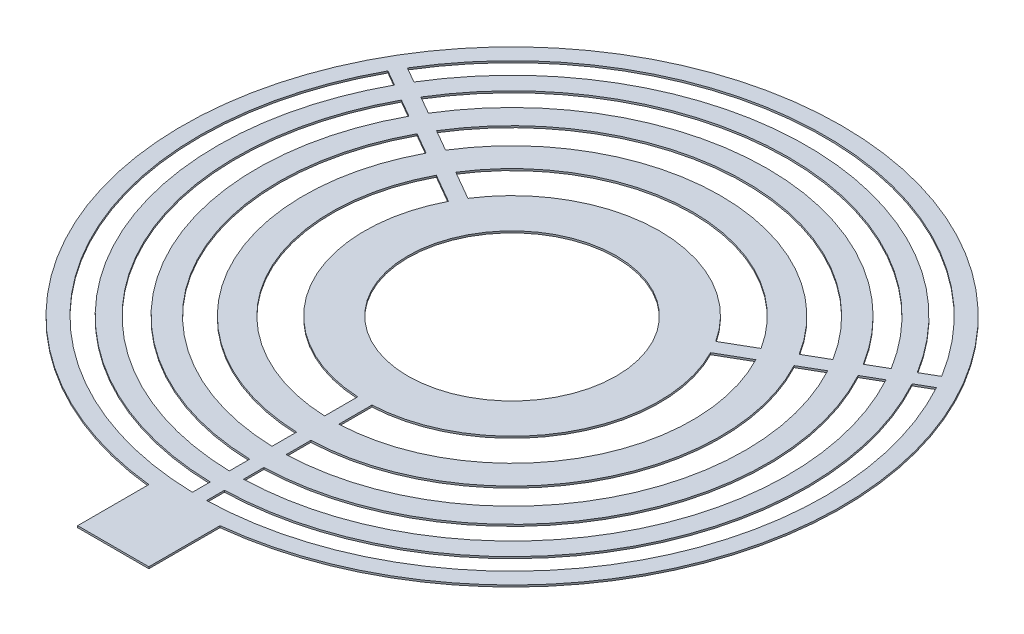
SolidWorks part; units mm, degrees
ref_plane "前视基准面" through (0, 0, 0) normal (0, 0, 1) x (1, 0, 0)
ref_plane "上视基准面" through (0, 0, 0) normal (0, 1, 0) x (1, 0, 0)
ref_plane "右视基准面" through (0, 0, 0) normal (1, 0, 0) x (0, 0, -1)
other "Configuration Table"
sketch "草图1" plane through (0, 0, 0) normal (0, 1, 0) x (1, 0, 0)
  line L0 (0, 0) -> (0, -29.29) construction
  line L1 (-2, -41.3717) -> (-2, -50.6906)
  line L2 (2, -41.3717) -> (2, -50.6906)
  line L3 (-10, -92.0886) -> (-10, -112.0886)
  line L4 (-10, -112.0886) -> (10, -112.0886)
  line L5 (10, -112.0886) -> (10, -92.0886)
  line L6 (-34.8289, 22.4179) -> (-42.8993, 27.0773)
  line L7 (-36.8289, 18.9538) -> (-44.8993, 23.6132)
  line L8 (36.8289, 18.9538) -> (44.8993, 23.6132)
  line L9 (34.8289, 22.4179) -> (42.8993, 27.0773)
  line L10 (51.7022, 27.5409) -> (57.6982, 31.0027)
  line L11 (49.7022, 31.005) -> (55.6982, 34.4668)
  line L12 (63.1132, 34.129) -> (68.0946, 37.005)
  line L13 (61.1132, 37.5931) -> (66.0946, 40.4691)
  line L14 (72.7293, 39.6809) -> (77.0779, 42.1916)
  line L15 (70.7293, 43.145) -> (75.0779, 45.6557)
  line L16 (-49.7022, 31.005) -> (-55.6982, 34.4668)
  line L17 (-51.7022, 27.5409) -> (-57.6982, 31.0027)
  line L18 (-61.1132, 37.5931) -> (-66.0946, 40.4691)
  line L19 (-63.1132, 34.129) -> (-68.0946, 37.005)
  line L20 (-70.7293, 43.145) -> (-75.0779, 45.6557)
  line L21 (-72.7293, 39.6809) -> (-77.0779, 42.1916)
  line L22 (-2, -58.5458) -> (-2, -65.4695)
  line L23 (2, -58.5458) -> (2, -65.4695)
  line L24 (2, -71.7221) -> (2, -77.4742)
  line L25 (-2, -71.7221) -> (-2, -77.4742)
  line L26 (2, -82.8259) -> (2, -87.8472)
  line L27 (-2, -82.8259) -> (-2, -87.8472)
  line L28 (0, -37.0978) -> (0, -55.5164) construction
  circle A0 centre (0, 0) radius 29.29
  arc A1 (2, -41.3717) -> (36.8289, 18.9538) centre (0, 0) ccw
  arc A2 (2, -50.6906) -> (44.8993, 23.6132) centre (0, 0) ccw
  arc A3 (2, -58.5458) -> (51.7022, 27.5409) centre (0, 0) ccw
  arc A4 (2, -65.4695) -> (57.6982, 31.0027) centre (0, 0) ccw
  arc A5 (2, -71.7221) -> (63.1132, 34.129) centre (0, 0) ccw
  arc A6 (2, -77.4742) -> (68.0946, 37.005) centre (0, 0) ccw
  arc A7 (2, -82.8259) -> (72.7293, 39.6809) centre (0, 0) ccw
  arc A8 (2, -87.8472) -> (77.0779, 42.1916) centre (0, 0) ccw
  arc A9 (10, -92.0886) -> (-10, -92.0886) centre (0, 0) ccw
  arc A10 (34.8289, 22.4179) -> (-34.8289, 22.4179) centre (0, 0) ccw
  arc A11 (42.8993, 27.0773) -> (-42.8993, 27.0773) centre (0, 0) ccw
  arc A12 (49.7022, 31.005) -> (-49.7022, 31.005) centre (0, 0) ccw
  arc A13 (55.6982, 34.4668) -> (-55.6982, 34.4668) centre (0, 0) ccw
  arc A14 (61.1132, 37.5931) -> (-61.1132, 37.5931) centre (0, 0) ccw
  arc A15 (66.0946, 40.4691) -> (-66.0946, 40.4691) centre (0, 0) ccw
  arc A16 (70.7293, 43.145) -> (-70.7293, 43.145) centre (0, 0) ccw
  arc A17 (75.0779, 45.6557) -> (-75.0779, 45.6557) centre (0, 0) ccw
  arc A18 (-36.8289, 18.9538) -> (-2, -41.3717) centre (0, 0) ccw
  arc A19 (-44.8993, 23.6132) -> (-2, -50.6906) centre (0, 0) ccw
  arc A20 (-51.7022, 27.5409) -> (-2, -58.5458) centre (0, 0) ccw
  arc A21 (-57.6982, 31.0027) -> (-2, -65.4695) centre (0, 0) ccw
  arc A22 (-63.1132, 34.129) -> (-2, -71.7221) centre (0, 0) ccw
  arc A23 (-68.0946, 37.005) -> (-2, -77.4742) centre (0, 0) ccw
  arc A24 (-72.7293, 39.6809) -> (-2, -82.8259) centre (0, 0) ccw
  arc A25 (-77.0779, 42.1916) -> (-2, -87.8472) centre (0, 0) ccw
  point P40 (0, 0)
  dimension "D1" = 185.26
  dimension "D2" = 175.74
  dimension "D3" = 165.7
  dimension "D4" = 155
  dimension "D5" = 143.5
  dimension "D6" = 131
  dimension "D7" = 117.16
  dimension "D8" = 101.46
  dimension "D9" = 82.84
  dimension "D10" = 58.58
  dimension "D11" = 4
  dimension "D12" = 20
  dimension "D13" = 20
  dimension "D15" = 120
  dimension "D14" = 3
extrude "凸台-拉伸1" add sketch "草图1" along normal blind 0.5
